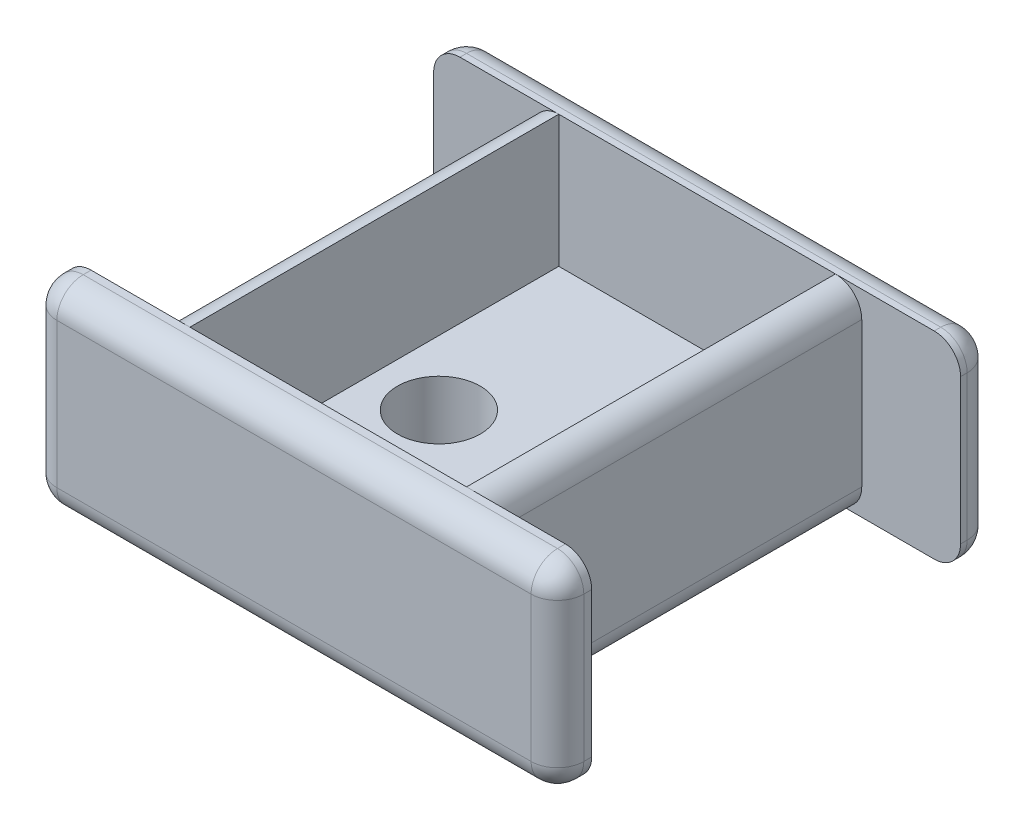
SolidWorks part; units mm, degrees
ref_plane "Front Plane" through (0, 0, 0) normal (0, 0, 1) x (1, 0, 0)
ref_plane "Top Plane" through (0, 0, 0) normal (0, 1, 0) x (1, 0, 0)
ref_plane "Right Plane" through (0, 0, 0) normal (1, 0, 0) x (0, 0, -1)
sketch "Sketch1" plane through (0, 0, 0) normal (0, 1, 0) x (1, 0, 0)
  line L0 (25.4, 20.955) -> (-25.4, 20.955)
  line L1 (-25.4, 20.955) -> (-25.4, 17.78)
  line L2 (25.4, 20.955) -> (25.4, 17.78)
  line L3 (25.4, 17.78) -> (15.875, 17.78)
  line L4 (15.875, 17.78) -> (15.875, -17.78)
  line L5 (15.875, -17.78) -> (25.4, -17.78)
  line L6 (25.4, -17.78) -> (25.4, -21.082)
  line L7 (25.4, -21.082) -> (-25.4, -21.082)
  line L8 (-25.4, -21.082) -> (-25.4, -17.78)
  line L9 (-25.4, -17.78) -> (-15.875, -17.78)
  line L10 (-15.875, -17.78) -> (-15.875, 17.78)
  line L11 (-15.875, 17.78) -> (-25.4, 17.78)
  line L12 (-15.875, 17.78) -> (15.875, -17.78) construction
  dimension "D1" = 50.8
  dimension "D2" = 35.56
  dimension "D3" = 3.302
  dimension "D4" = 3.175
  dimension "D5" = 31.75
extrude "Boss-Extrude1" add sketch "Sketch1" along normal blind 19.05
sketch "Sketch4" plane through (0, 19.05, 0) normal (0, 1, 0) x (1, 0, 0)
  circle A0 centre (6.985, 0) radius 4.064
  circle A1 centre (-7.112, 0) radius 4.0005
  dimension "D1" = 8.128
  dimension "D2" = 8.001
  dimension "D4" = 6.985
  dimension "D3" = 7.112
extrude "Cut-Extrude3" cut sketch "Sketch4" against normal blind 38.1
fillet "Fillet8" radius 2.54 8 edges at (0, 0, -20.955) (-15.875, 0, 0) (15.875, 0, 0) (0, 0, 21.082) (15.875, 19.05, 0) (0, 19.05, -20.955) (-15.875, 19.05, 0) (0, 19.05, 21.082)
fillet "Fillet9" radius 2.54 20 edges at (-25.4, 9.525, 21.082) (-25.4, 18.3061, 20.3381) (-25.4, 9.525, -20.955) (-25.4, 18.3061, -20.2111) (25.4, 9.525, -20.955) (25.4, 18.3061, -20.2111) (25.4, 9.525, 21.082) (25.4, 18.3061, 20.3381) (-25.4, 19.05, 18.161) (-25.4, 19.05, -18.0975) (25.4, 19.05, -18.0975) (25.4, 19.05, 18.161) (-25.4, 0, 18.161) (-25.4, 0.7439, 20.3381) (-25.4, 0, -18.0975) (-25.4, 0.7439, -20.2111) (25.4, 0, -18.0975) (25.4, 0.7439, -20.2111) (25.4, 0, 18.161) (25.4, 0.7439, 20.3381)
sketch "Sketch9" plane through (0, 19.05, 0) normal (0, 1, 0) x (1, 0, 0)
  line L0 (-13.335, 17.78) -> (-13.335, -17.78) construction
  line L1 (-13.335, 17.78) -> (13.335, 17.78)
  line L2 (-13.335, 17.78) -> (-13.335, -17.78)
  line L3 (-13.335, -17.78) -> (13.335, -17.78)
  line L4 (13.335, 17.78) -> (13.335, -17.78)
  dimension "D1" = 35.56
extrude "Cut-Extrude6" cut sketch "Sketch9" against normal blind 12.7
sketch "Sketch10" plane through (-15.875, 0, 0) normal (-1, 0, 0) x (0, 0, 1)
  line L0 (-14.0836, 6.4731) -> (12.7717, 6.4731) construction
  text T0 "FUTURE" font "Engravers MT" height 3.5
extrude "Boss-Extrude2" add sketch "Sketch10" along normal blind 0.254
